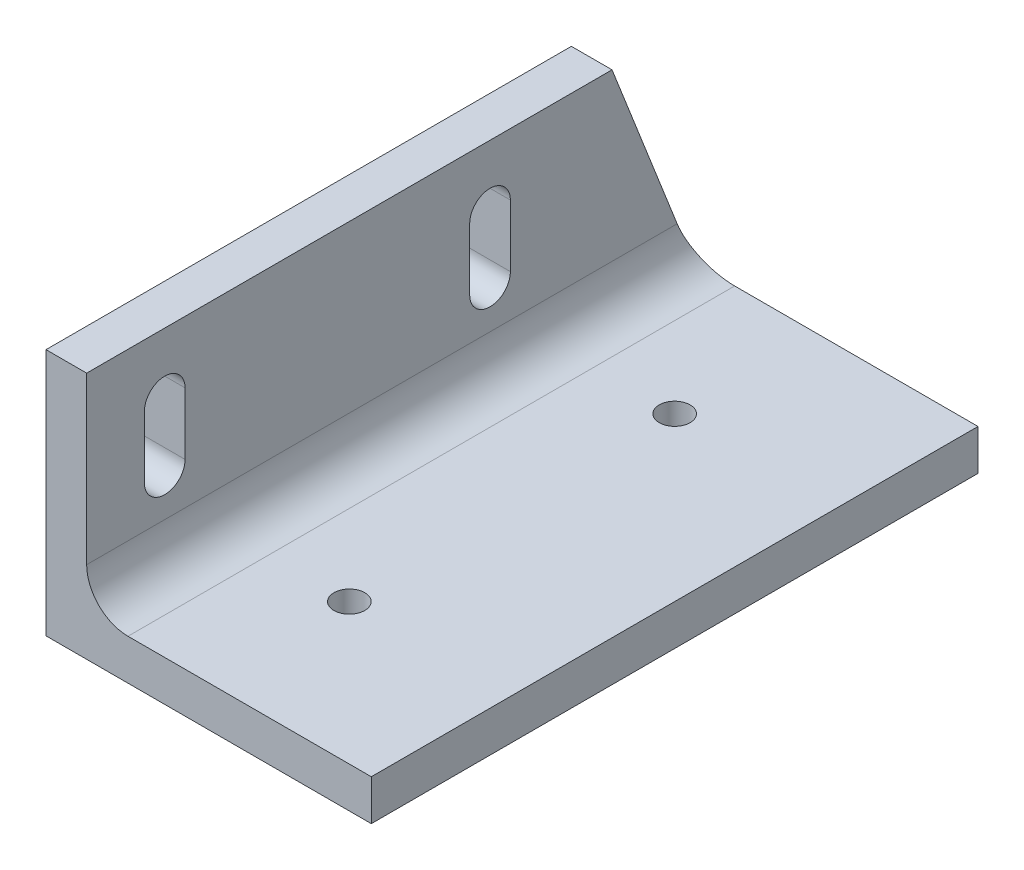
SolidWorks part; units mm, degrees
ref_plane "Front Plane" through (0, 0, 0) normal (0, 0, 1) x (1, 0, 0)
ref_plane "Top Plane" through (0, 0, 0) normal (0, 1, 0) x (1, 0, 0)
ref_plane "Right Plane" through (0, 0, 0) normal (1, 0, 0) x (0, 0, -1)
sketch "Sketch1" plane through (0, 0, 0) normal (0, 0, 1) x (1, 0, 0)
  line L0 (0, 25.48) -> (0, 0)
  line L1 (0, 0) -> (35, 0)
  line L2 (35, 0) -> (35, -5)
  line L3 (35, -5) -> (-5, -5)
  line L4 (-5, -5) -> (-5, 25.48)
  line L5 (-5, 25.48) -> (0, 25.48)
  dimension "D1" = 30.48
extrude "Boss-Extrude1" add sketch "Sketch1" along normal blind 74.6
sketch "Sketch2" plane through (0, 0, 0) normal (0, 1, 0) x (1, 0, 0)
  line L0 (35, -74.6) -> (0, -74.6) construction
  line L2 (-5, -74.6) -> (-5, 0) construction
  circle A0 centre (15, -57.3) radius 0.5
  circle A1 centre (15, -17.3) radius 0.5
  point P5 (17.5, -74.6)
  dimension "D1" = 17.3
  dimension "D4" = 1
  dimension "D2" = 40
  dimension "D3" = 20
sketch "Sketch3" plane through (0, 0, 0) normal (1, 0, 0) x (0, 0, -1)
  line L0 (-65, 10.24) -> (-65, 17.86) construction
  line L1 (-67.5, 10.24) -> (-67.5, 17.86)
  line L2 (-62.5, 10.24) -> (-62.5, 17.86)
  line L3 (-25, 10.24) -> (-25, 17.86) construction
  line L4 (-27.5, 10.24) -> (-27.5, 17.86)
  line L5 (-22.5, 10.24) -> (-22.5, 17.86)
  line L6 (-74.6, -5) -> (0, -5) construction
  line L9 (0, 25.48) -> (0, -5) construction
  arc A0 (-67.5, 10.24) -> (-62.5, 10.24) centre (-65, 10.24) ccw
  arc A1 (-62.5, 17.86) -> (-67.5, 17.86) centre (-65, 17.86) ccw
  arc A2 (-27.5, 10.24) -> (-22.5, 10.24) centre (-25, 10.24) ccw
  arc A3 (-22.5, 17.86) -> (-27.5, 17.86) centre (-25, 17.86) ccw
  point P2 (-65, 14.05)
  point P9 (-25, 14.05)
  dimension "D1" = 15.24
  dimension "D3" = 2.5
  dimension "D2" = 22.86
  dimension "D4" = 25
  dimension "D5" = 40
extrude "Cut-Extrude2" cut sketch "Sketch3" against normal through all
sketch "Sketch4" plane through (0, 0, 0) normal (1, 0, 0) x (0, 0, -1)
  line L0 (0, 0) -> (-10, 25.48)
  line L1 (-74.6, 25.48) -> (0, 25.48) construction
  line L2 (-10, 25.48) -> (0, 25.48)
  line L3 (0, 25.48) -> (0, 0)
  line L4 (-10, 25.48) -> (0, 25.48)
  line L5 (0, 0) -> (0, 25.48)
  line M10 (0, 0) -> (0, 25.48)
  line M11 (0, 25.48) -> (-74.6, 25.48)
extrude "Cut-Extrude3" cut sketch "Sketch4" against normal blind 10 contours L0 M10 M11
fillet "Fillet1" radius 5.08 1 edges at (0, 0, 37.3)
hole_wizard "#10-24 Tapped Hole1" positions "Sketch6" profile "Sketch5" tap size "#10-24" standard "ANSI Inch" end condition through all
sketch "Sketch6" plane through (0, 0, 0) normal (0, 1, 0) x (1, 0, 0)
  point P0 (15, -17.3)
  point P3 (15, -57.3)
sketch "Sketch5" plane through (15, 0, 17.3) normal (1, 0, 0) x (0, 0, 1)
  line L0 (0, 0) -> (0, 5)
  line L1 (0, 5) -> (1.8986, 5)
  line L2 (1.8986, 5) -> (1.8986, 0)
  line L5 (1.8986, 0) -> (0, 0)
  line L11 (0, -6.35) -> (0, 107.95) construction
  dimension "Thru Tap Drill Dia." = 3.7973
  dimension "Thru Tap Drill Depth" = 5
cosmetic thread "Hole Thread1" parameters "D2"=4.826
cosmetic thread "Hole Thread2" parameters "D2"=4.826
